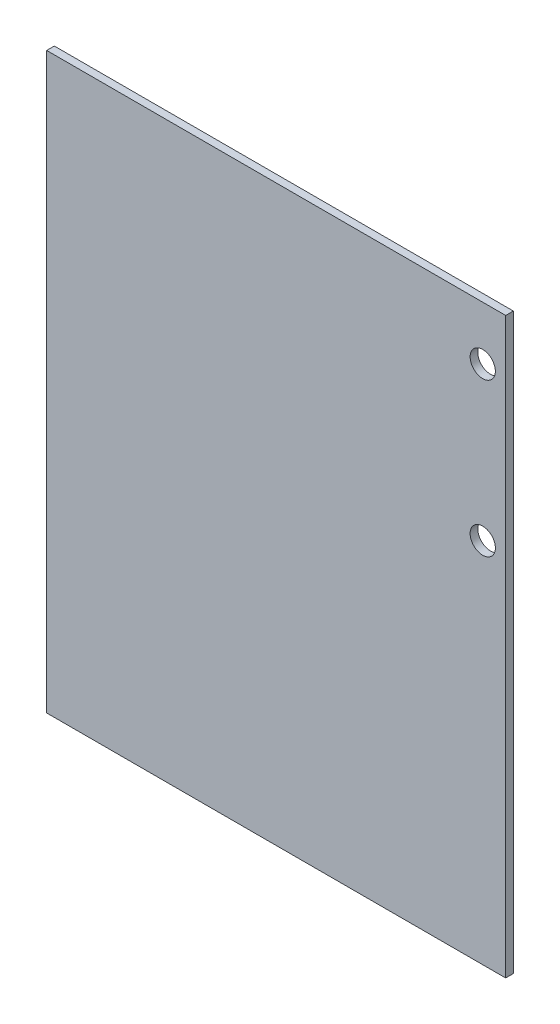
SolidWorks part; units mm, degrees
material "环氧板"
ref_plane "前视基准面" through (0, 0, 0) normal (0, 0, 1) x (1, 0, 0)
ref_plane "上视基准面" through (0, 0, 0) normal (0, 1, 0) x (1, 0, 0)
ref_plane "右视基准面" through (0, 0, 0) normal (1, 0, 0) x (0, 0, -1)
other "Configuration Table"
sketch "草图1" plane through (0, 0, 0) normal (0, 0, 1) x (1, 0, 0)
  line L1 (-30, 37.5) -> (30, 37.5)
  line L2 (-30, 37.5) -> (-30, -37.5)
  line L3 (-30, -37.5) -> (30, -37.5)
  line L4 (30, 37.5) -> (30, -37.5)
  line L5 (-30, 37.5) -> (30, -37.5) construction
  line L6 (-30, -37.5) -> (30, 37.5) construction
  point P0 (0, 0)
  dimension "D1" = 75
  dimension "D2" = 60
extrude "凸台-拉伸1" add sketch "草图1" along normal blind 1
sketch "草图3" plane through (0, 0, 1) normal (0, 0, 1) x (1, 0, 0)
  line L0 (30, 37.5) -> (-30, 37.5) construction
  line L1 (30, -37.5) -> (30, 37.5) construction
  circle A0 centre (27, 30.5) radius 1.65
  circle A1 centre (27, 10.5) radius 1.65
  dimension "D1" = 7
  dimension "D2" = 3.3
  dimension "D4" = 20
  dimension "D3" = 3
extrude "切除-拉伸1" cut sketch "草图3" against normal through all
